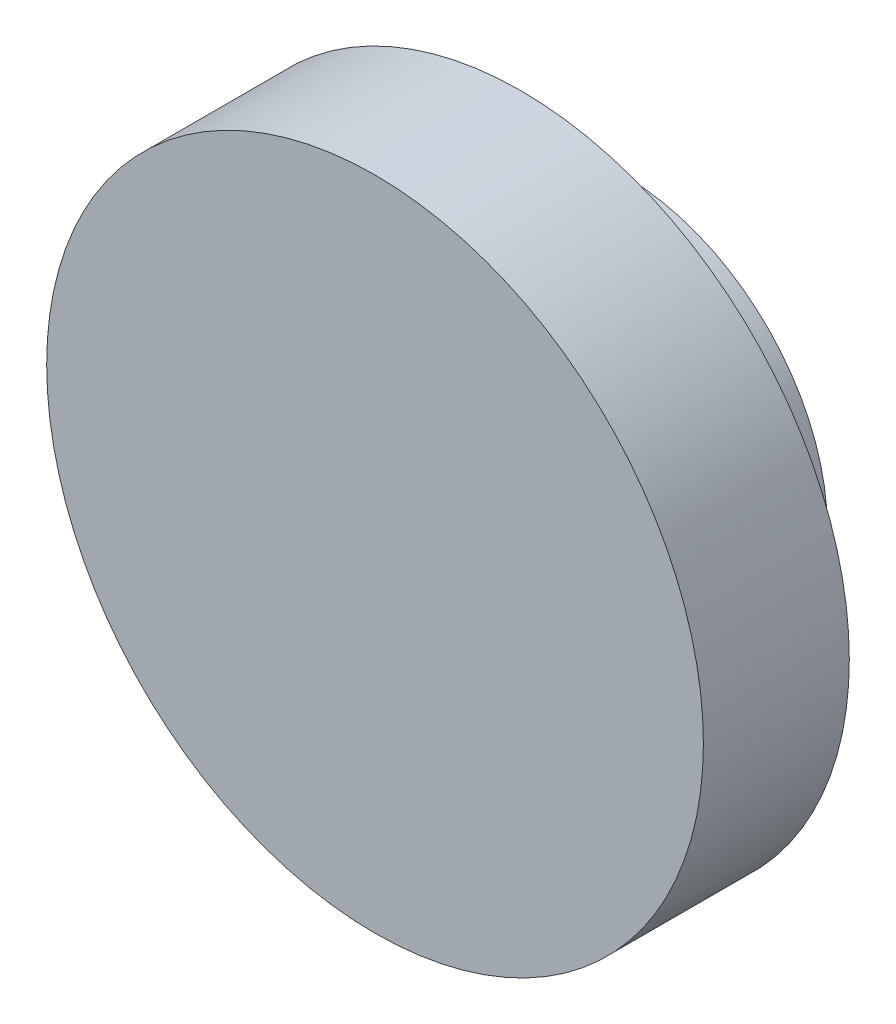
SolidWorks part; units mm, degrees
ref_plane "前视基准面" through (0, 0, 0) normal (0, 0, 1) x (1, 0, 0)
ref_plane "上视基准面" through (0, 0, 0) normal (0, 1, 0) x (1, 0, 0)
ref_plane "右视基准面" through (0, 0, 0) normal (1, 0, 0) x (0, 0, -1)
other "Configuration Table"
sketch "草图1" plane through (0, 0, 0) normal (0, 0, 1) x (1, 0, 0)
  circle A0 centre (0, 0) radius 12.25
  circle A1 centre (0, 0) radius 14
  dimension "D1" = 24.5
  dimension "D2" = 28
extrude "凸台-拉伸1" add sketch "草图1" along normal mid plane 6
sketch "草图2" plane through (0, 0, 3) normal (0, 0, 1) x (1, 0, 0)
  circle A0 centre (0, 0) radius 12.25
  circle A1 centre (0, 0) radius 15.963
extrude "凸台-拉伸2" add sketch "草图2" along normal blind 1
sketch "草图3" plane through (0, 0, 4) normal (0, 0, 1) x (1, 0, 0)
  circle A0 centre (0, 0) radius 22.5
  dimension "D1" = 45
extrude "凸台-拉伸3" add sketch "草图3" along normal blind 10
